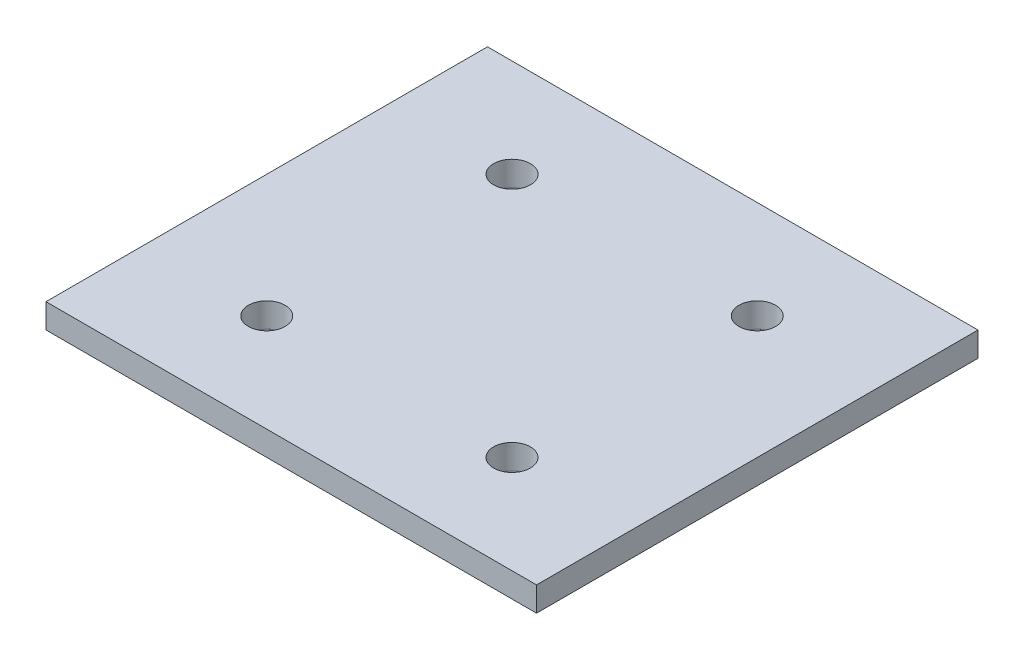
SolidWorks part; units mm, degrees
ref_plane "前视基准面" through (0, 0, 0) normal (0, 0, 1) x (1, 0, 0)
ref_plane "上视基准面" through (0, 0, 0) normal (0, 1, 0) x (1, 0, 0)
ref_plane "右视基准面" through (0, 0, 0) normal (1, 0, 0) x (0, 0, -1)
other "Configuration Table"
sketch "草图1" plane through (0, 0, 0) normal (0, 1, 0) x (1, 0, 0)
  line L1 (20, -18) -> (-20, -18)
  line L2 (20, -18) -> (20, 18)
  line L3 (20, 18) -> (-20, 18)
  line L4 (-20, -18) -> (-20, 18)
  line L5 (20, -18) -> (-20, 18) construction
  line L6 (20, 18) -> (-20, -18) construction
  line L7 (10, -10) -> (-10, -10) construction
  line L8 (10, -10) -> (10, 10) construction
  line L9 (10, 10) -> (-10, 10) construction
  line L10 (-10, -10) -> (-10, 10) construction
  line L11 (10, -10) -> (-10, 10) construction
  line L12 (10, 10) -> (-10, -10) construction
  circle A0 centre (-10, 10) radius 1.5
  circle A1 centre (10, 10) radius 1.5
  circle A2 centre (10, -10) radius 1.5
  circle A3 centre (-10, -10) radius 1.5
  point P0 (0, 0)
  point P6 (0, 0)
  point P12 (0, 0)
  point P21 (0, 0)
  dimension "D5" = 3
  dimension "D1" = 40
  dimension "D2" = 36
  dimension "D3" = 20
  dimension "D4" = 20
  dimension "D6" = 4
extrude "凸台-拉伸1" add sketch "草图1" along normal blind 2
sketch "草图2" plane through (0, 0, 0) normal (0, -1, 0) x (1, 0, 0)
  line L0 (0, 0) -> (4.9588, 0) construction
  line L1 (0, 0) -> (0, 3.528) construction
  circle A0 centre (-10, 10) radius 3
  circle A1 centre (-10, 10) radius 1.5 construction
  circle A2 centre (-10, 10) radius 1.5
  circle A3 centre (10, 10) radius 1.5
  circle A4 centre (10, 10) radius 3
  circle A5 centre (10, -10) radius 3
  circle A6 centre (10, -10) radius 1.5
  circle A7 centre (-10, -10) radius 1.5
  circle A8 centre (-10, -10) radius 3
  dimension "D1" = 6
extrude "凸台-拉伸2" add sketch "草图2" along normal blind 5 separate body
